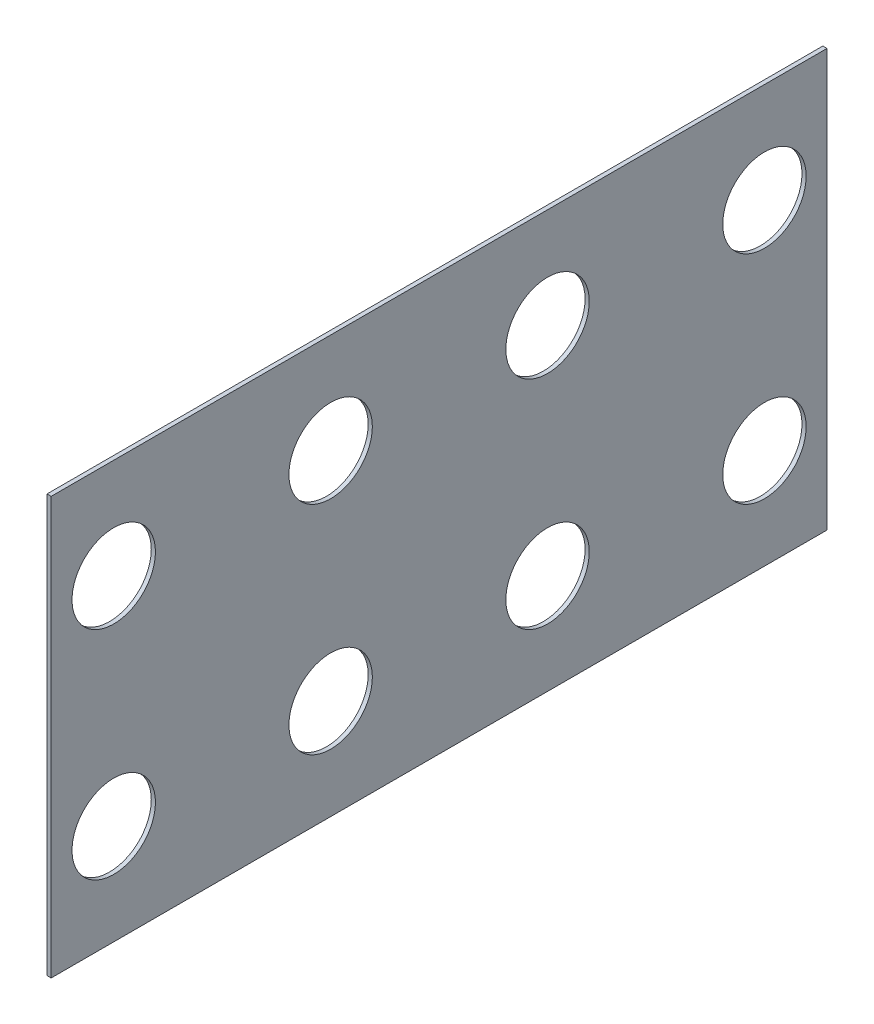
SolidWorks part; units mm, degrees
ref_plane "Alzado" through (0, 0, 0) normal (0, 0, 1) x (1, 0, 0)
ref_plane "Planta" through (0, 0, 0) normal (0, 1, 0) x (1, 0, 0)
ref_plane "Vista lateral" through (0, 0, 0) normal (1, 0, 0) x (0, 0, -1)
sketch "Croquis1" plane through (0, 0, 0) normal (1, 0, 0) x (0, 0, -1)
  line L1 (465, -250) -> (-465, -250)
  line L2 (465, -250) -> (465, 250)
  line L3 (465, 250) -> (-465, 250)
  line L4 (-465, -250) -> (-465, 250)
  line L5 (465, -250) -> (-465, 250) construction
  line L6 (465, 250) -> (-465, -250) construction
  point P0 (0, 0)
  dimension "D1" = 930
  dimension "D2" = 500
extrude "Extruir1" add sketch "Croquis1" along normal blind 5
sketch "Croquis2" plane through (5, 0, 0) normal (1, 0, 0) x (0, 0, -1)
  line L0 (-445, -250) -> (-445, 250) construction
  line L1 (-465, -250) -> (465, -250) construction
  line L2 (465, 250) -> (-465, 250) construction
  line L4 (-445, 0) -> (445, 0) construction
  line L5 (445, 250) -> (445, -250) construction
  line L6 (0, 0) -> (0, -250) construction
  line L7 (-465, 230) -> (465, 230) construction
  line L8 (-465, 250) -> (-465, -250) construction
  line L9 (465, -250) -> (465, 250) construction
  circle A0 centre (-445, -210) radius 10
  circle A1 centre (445, -210) radius 10
  circle A2 centre (-315, 230) radius 10
  circle A3 centre (315, 230) radius 10
  circle A4 centre (445, 210) radius 10
  circle A5 centre (-445, 210) radius 10
  dimension "D2" = 20
  dimension "D3" = 40
  dimension "D5" = 150
  dimension "D1" = 890
  dimension "D4" = 20
sketch "Croquis3" plane through (5, 0, 0) normal (1, 0, 0) x (0, 0, -1)
  line L0 (-445, 0) -> (445, 0) construction
  line L1 (0, 0) -> (0, -250) construction
  circle A0 centre (-390, 390) radius 50
  circle A1 centre (-130, 390) radius 50
  circle A2 centre (130, 390) radius 50
  circle A3 centre (390, 390) radius 50
  circle A4 centre (-390, 130) radius 50
  circle A5 centre (-130, 130) radius 50
  circle A6 centre (130, 130) radius 50
  circle A7 centre (390, 130) radius 50
  circle A8 centre (-390, -130) radius 50
  circle A9 centre (-130, -130) radius 50
  circle A10 centre (130, -130) radius 50
  circle A11 centre (390, -130) radius 50
  circle A12 centre (-390, -390) radius 50
  circle A13 centre (-130, -390) radius 50
  circle A14 centre (130, -390) radius 50
  circle A15 centre (390, -390) radius 50
  point P0 (-390, 390)
  dimension "D3" = 100
  dimension "D1" = 390
  dimension "D2" = 390
extrude "Extruir2" cut sketch "Croquis3" against normal through all
